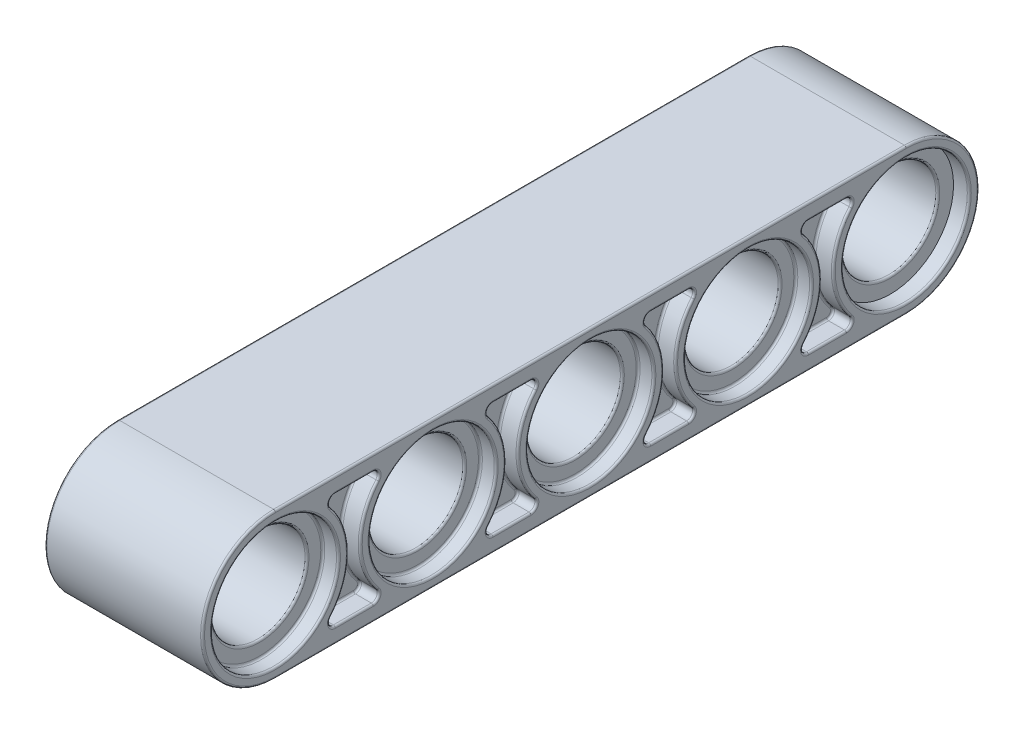
SolidWorks part; units mm, degrees
ref_plane "Front Plane" through (0, 0, 0) normal (0, 0, 1) x (1, 0, 0)
ref_plane "Top Plane" through (0, 0, 0) normal (0, 1, 0) x (1, 0, 0)
ref_plane "Right Plane" through (0, 0, 0) normal (1, 0, 0) x (0, 0, -1)
sketch "Sketch1" plane through (0, 0, 0) normal (1, 0, 0) x (0, 0, -1)
  line L0 (-15.5646, 0) -> (16.4354, 0) construction
  line L1 (-15.5646, 3.7) -> (16.4354, 3.7)
  line L2 (-15.5646, -3.7) -> (16.4354, -3.7)
  arc A0 (-15.5646, 3.7) -> (-15.5646, -3.7) centre (-15.5646, 0) ccw
  arc A1 (16.4354, -3.7) -> (16.4354, 3.7) centre (16.4354, 0) ccw
  circle A2 centre (-15.5646, 0) radius 2.4
  circle A3 centre (-7.5646, 0) radius 2.4
  circle A4 centre (0.4354, 0) radius 2.4
  circle A5 centre (8.4354, 0) radius 2.4
  circle A6 centre (16.4354, 0) radius 2.4
  point P3 (0.4354, 0)
  dimension "D3" = 5
  dimension "D1" = 7.4
  dimension "D2" = 32
extrude "Boss-Extrude1" add sketch "Sketch1" along normal blind 8
sketch "Sketch2" plane through (8, 0, 0) normal (1, 0, 0) x (0, 0, -1)
  circle A0 centre (-15.5646, 0) radius 3.2
  circle A1 centre (-7.5646, 0) radius 3.2
  circle A2 centre (0.4354, 0) radius 3.2
  circle A3 centre (8.4354, 0) radius 3.2
  circle A4 centre (16.4354, 0) radius 3.2
  dimension "D1" = 5
extrude "Cut-Extrude1" cut sketch "Sketch2" against normal blind 0.8
sketch "Sketch4" plane through (8, 0, 0) normal (1, 0, 0) x (0, 0, -1)
  line L0 (-12.5249, 2.9) -> (-10.6044, 2.9)
  line L1 (16.4354, 3.7) -> (-15.5646, 3.7) construction
  line L2 (-15.5646, 0) -> (-23.3024, 0) construction
  line L3 (-12.5249, -2.9) -> (-10.6044, -2.9)
  line L4 (-4.5249, 2.9) -> (-2.6044, 2.9)
  line L5 (-4.5249, -2.9) -> (-2.6044, -2.9)
  line L6 (3.4751, 2.9) -> (5.3956, 2.9)
  line L7 (3.4751, -2.9) -> (5.3956, -2.9)
  line L8 (11.4751, 2.9) -> (13.3956, 2.9)
  line L9 (11.4751, -2.9) -> (13.3956, -2.9)
  arc A0 (-12.7529, -2.405) -> (-12.7529, 2.405) centre (-15.5646, 0) ccw
  arc A1 (-10.3764, 2.405) -> (-10.3764, -2.405) centre (-7.5646, 0) ccw
  arc A2 (-12.7529, -2.405) -> (-12.5249, -2.9) centre (-12.5249, -2.6) ccw
  arc A3 (-10.3764, -2.405) -> (-10.6044, -2.9) centre (-10.6044, -2.6) cw
  arc A4 (-10.6044, 2.9) -> (-10.3764, 2.405) centre (-10.6044, 2.6) cw
  arc A5 (-12.7529, 2.405) -> (-12.5249, 2.9) centre (-12.5249, 2.6) cw
  arc A6 (-4.7529, -2.405) -> (-4.7529, 2.405) centre (-7.5646, 0) ccw
  arc A7 (-2.3764, 2.405) -> (-2.3764, -2.405) centre (0.4354, 0) ccw
  arc A8 (-4.7529, -2.405) -> (-4.5249, -2.9) centre (-4.5249, -2.6) ccw
  arc A9 (-2.3764, -2.405) -> (-2.6044, -2.9) centre (-2.6044, -2.6) cw
  arc A10 (-2.6044, 2.9) -> (-2.3764, 2.405) centre (-2.6044, 2.6) cw
  arc A11 (-4.7529, 2.405) -> (-4.5249, 2.9) centre (-4.5249, 2.6) cw
  arc A12 (3.2471, -2.405) -> (3.2471, 2.405) centre (0.4354, 0) ccw
  arc A13 (5.6236, 2.405) -> (5.6236, -2.405) centre (8.4354, 0) ccw
  arc A14 (3.2471, -2.405) -> (3.4751, -2.9) centre (3.4751, -2.6) ccw
  arc A15 (5.6236, -2.405) -> (5.3956, -2.9) centre (5.3956, -2.6) cw
  arc A16 (5.3956, 2.9) -> (5.6236, 2.405) centre (5.3956, 2.6) cw
  arc A17 (3.2471, 2.405) -> (3.4751, 2.9) centre (3.4751, 2.6) cw
  arc A18 (11.2471, -2.405) -> (11.2471, 2.405) centre (8.4354, 0) ccw
  arc A19 (13.6236, 2.405) -> (13.6236, -2.405) centre (16.4354, 0) ccw
  arc A20 (11.2471, -2.405) -> (11.4751, -2.9) centre (11.4751, -2.6) ccw
  arc A21 (13.6236, -2.405) -> (13.3956, -2.9) centre (13.3956, -2.6) cw
  arc A22 (13.3956, 2.9) -> (13.6236, 2.405) centre (13.3956, 2.6) cw
  arc A23 (11.2471, 2.405) -> (11.4751, 2.9) centre (11.4751, 2.6) cw
  dimension "D3" = 0.3
  dimension "D2" = 0.8
  dimension "D1" = 2
  dimension "D4" = 4
extrude "Cut-Extrude2" cut sketch "Sketch4" against normal blind 1
ref_plane "Plane1" through (4, 0, 0) normal (1, 0, 0) x (0, 0, -1)
mirror "Mirror1" about plane through (4, 0, 0) normal (1, 0, 0) of "Cut-Extrude2", "Cut-Extrude1"
fillet "Fillet1" radius 0.1 123 edges at (0, -3.7, -0.4354) (0, 0, -20.1354) (1, -2.9, -12.4354) (1, -2.7255, -13.6681) (1, 0, -12.7354) (1, 2.7255, -13.6681) (1, 2.9, -12.4354) (1, 2.7255, -11.2026) (1, 0, -12.1354) (1, -2.7255, -11.2026) (0, 0, 19.2646) (0.8, 0, -19.6354) (0.8, 0, -11.6354) (1, -2.9, -4.4354) (1, -2.7255, -5.6681) (1, 0, -4.7354) (1, 2.7255, -5.6681) (1, 2.9, -4.4354) (1, 2.7255, -3.2026) (1, 0, -4.1354) (1, -2.7255, -3.2026) (0.8, 0, -3.6354) (1, -2.9, 3.5646) (1, -2.7255, 2.3319) (1, 0, 3.2646) (1, 2.7255, 2.3319) (1, 2.9, 3.5646) (1, 2.7255, 4.7974) (0.8, 0, 4.3646) (1, -2.9, 11.5646) (1, -2.7255, 10.3319) (1, 0, 11.2646) (1, 2.7255, 10.3319) (1, 2.7255, 12.7974) (1, 0, 11.8646) (1, -2.7255, 12.7974) (0.8, 0, 12.3646) (0, 3.7, -0.4354) (0.8, 0, -14.0354) (7.2, 0, -18.8354) (7, 0, -12.1354) (7, 2.7255, -11.2026) (7, 2.9, -12.4354) (7, 0, -12.7354) (7, -2.7255, -13.6681) (7, -2.9, -12.4354) (7, -2.7255, -11.2026) (0.8, 0, -6.0354) (7.2, 0, -11.6354) (7.2, 0, -10.8354) (7, 0, -4.1354) (7, 2.7255, -3.2026) (7, 2.9, -4.4354) (7, 2.7255, -5.6681) (7, 0, -4.7354) (7, -2.7255, -5.6681) (7, -2.9, -4.4354) (7, -2.7255, -3.2026) (0.8, 0, 1.9646) (7.2, 0, -3.6354) (7.2, 0, -2.8354) (7, 0, 3.8646) (7, 2.7255, 4.7974) (7, 2.9, 3.5646) (7, 2.7255, 2.3319) (7, 0, 3.2646) (7, -2.7255, 2.3319) (7, -2.9, 3.5646) (7, -2.7255, 4.7974) (0.8, 0, 9.9646) (7.2, 0, 4.3646) (7.2, 0, 5.1646) (7, 0, 11.8646) (7, 2.7255, 12.7974) (7, 2.7255, 10.3319) (7, 0, 11.2646) (7, -2.7255, 10.3319) (7, -2.9, 11.5646) (7, -2.7255, 12.7974) (7.2, 0, 12.3646) (0.8, 0, 17.9646) (7.2, 0, 13.1646) (8, 3.7, -0.4354) (8, 0, -20.1354) (8, -3.7, -0.4354) (8, 0, 19.2646) (8, 0, 12.3646) (8, 0, 4.3646) (8, 0, -3.6354) (8, 0, -11.6354) (8, 0, -19.6354) (8, -2.9, 11.5646) (8, -2.7255, 10.3319) (8, 0, 11.2646) (8, 2.7255, 10.3319) (8, 2.9, 11.5646) (8, 2.7255, 12.7974) (8, 0, 11.8646) (8, -2.7255, 12.7974) (8, -2.9, 3.5646) (8, -2.7255, 2.3319) (8, 0, 3.2646) (8, 2.7255, 2.3319) (8, 2.9, 3.5646) (8, 2.7255, 4.7974) (8, 0, 3.8646) (8, -2.7255, 4.7974) (8, -2.9, -4.4354) (8, -2.7255, -5.6681) (8, 0, -4.7354) (8, 2.7255, -5.6681) (8, 2.9, -4.4354) (8, 2.7255, -3.2026) (8, 0, -4.1354) (8, -2.7255, -3.2026) (8, -2.9, -12.4354) (8, -2.7255, -13.6681) (8, 0, -12.7354) (8, 2.7255, -13.6681) (8, 2.9, -12.4354) (8, 2.7255, -11.2026) (8, 0, -12.1354) (8, -2.7255, -11.2026)
fillet "Fillet2" radius 0.1 37 edges at (0, 0, -12.1354) (0, 2.7255, -11.2026) (0, 2.9, -12.4354) (0, 2.7255, -13.6681) (0, 0, -12.7354) (0, -2.7255, -13.6681) (0, -2.9, -12.4354) (0, -2.7255, -11.2026) (0, 0, 3.8646) (0, 2.7255, 4.7974) (0, 2.9, 3.5646) (0, 2.7255, 2.3319) (0, 0, 3.2646) (0, -2.7255, 2.3319) (0, -2.9, 3.5646) (0, -2.7255, 4.7974) (0, 0, -19.6354) (0, 0, -3.6354) (0, 0, 12.3646) (0, 0, 4.3646) (0, 0, -11.6354) (0, 0, 11.8646) (0, 2.7255, 12.7974) (0, 2.9, 11.5646) (0, 2.7255, 10.3319) (0, 0, 11.2646) (0, -2.7255, 10.3319) (0, -2.9, 11.5646) (0, -2.7255, 12.7974) (0, 0, -4.1354) (0, 2.7255, -3.2026) (0, 2.9, -4.4354) (0, 2.7255, -5.6681) (0, 0, -4.7354) (0, -2.7255, -5.6681) (0, -2.9, -4.4354) (0, -2.7255, -3.2026)
